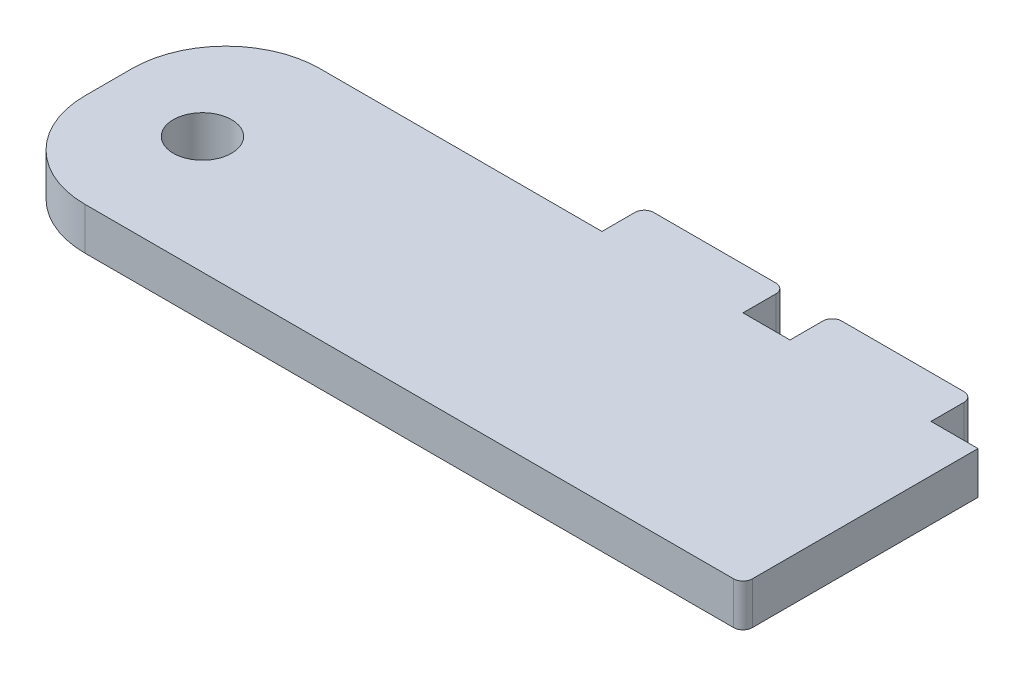
SolidWorks part; units mm, degrees
ref_plane "Front Plane" through (0, 0, 0) normal (0, 0, 1) x (1, 0, 0)
ref_plane "Top Plane" through (0, 0, 0) normal (0, 1, 0) x (1, 0, 0)
ref_plane "Right Plane" through (0, 0, 0) normal (1, 0, 0) x (0, 0, -1)
sketch "Sketch1" plane through (0, 0, 0) normal (0, 1, 0) x (1, 0, 0)
  line L0 (-30, 12.5) -> (-30, -12.5) construction
  line L1 (-30, -12.5) -> (39, -12.5)
  line L2 (-40, -2.5) -> (-40, 2.5)
  line L3 (-30, 12.5) -> (0, 12.5)
  line L4 (40, -11.5) -> (40, 12.5)
  line L5 (-40, -12.5) -> (40, 12.5) construction
  line L6 (-40, 12.5) -> (40, -12.5) construction
  line L7 (15, 12.5) -> (20, 12.5)
  line L8 (35, 12.5) -> (40, 12.5)
  line L9 (0, 12.5) -> (0, 16)
  line L10 (1, 17) -> (14, 17)
  line L11 (15, 12.5) -> (15, 16)
  line L13 (20, 12.5) -> (20, 16)
  line L14 (21, 17) -> (34, 17)
  line L15 (35, 12.5) -> (35, 16)
  circle A0 centre (-30, 0) radius 3.1
  arc A1 (34, 17) -> (35, 16) centre (34, 16) cw
  arc A2 (20, 16) -> (21, 17) centre (21, 16) cw
  arc A3 (14, 17) -> (15, 16) centre (14, 16) cw
  arc A4 (0, 16) -> (1, 17) centre (1, 16) cw
  arc A5 (-30, -12.5) -> (-40, -2.5) centre (-30, -2.5) cw
  arc A6 (-40, 2.5) -> (-30, 12.5) centre (-30, 2.5) cw
  arc A7 (39, -12.5) -> (40, -11.5) centre (39, -11.5) ccw
  point P0 (0, 0)
  point P20 (35, 17)
  point P23 (20, 17)
  point P26 (15, 17)
  point P29 (0, 17)
  dimension "D4" = 4.5
  dimension "D9" = 1
  dimension "D10" = 10
  dimension "D11" = 1
  dimension "D1" = 80
  dimension "D2" = 25
  dimension "D3" = 10
  dimension "D5" = 30
  dimension "D6" = 15
  dimension "D7" = 15
  dimension "D8" = 5
extrude "Boss-Extrude1" add sketch "Sketch1" along normal blind 4.5
